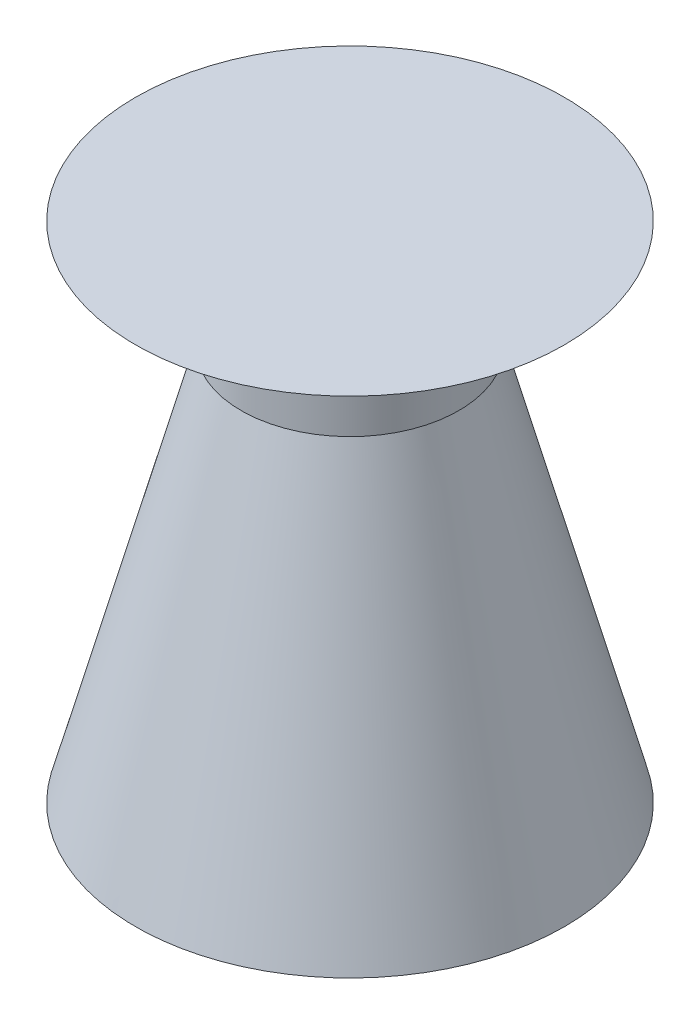
SolidWorks part; units mm, degrees
material "Copper"
ref_plane "Front Plane" through (0, 0, 0) normal (0, 0, 1) x (1, 0, 0)
ref_plane "Top Plane" through (0, 0, 0) normal (0, 1, 0) x (1, 0, 0)
ref_plane "Right Plane" through (0, 0, 0) normal (1, 0, 0) x (0, 0, -1)
sketch "Sketch1" plane through (0, 0, 0) normal (0, 0, 1) x (1, 0, 0)
  line L6 (0, 32.8219) -> (0, -32.8219)
  line L8 (27.94, 32.8219) -> (14.1808, 24.878)
  line L9 (14.1808, 24.878) -> (14.1808, 18.528)
  line L10 (14.1808, 18.528) -> (27.94, -32.8219)
  line L12 (0, 32.8219) -> (27.94, 32.8219)
  line L13 (0, -32.8219) -> (27.94, -32.8219)
  point P4 (0, 0)
  dimension "D1" = 14.1808
  dimension "D2" = 27.94
  dimension "D3" = 15.8877
  dimension "D4" = 6.35
  dimension "D5" = 15
  dimension "D6" = 27.94
revolve "Revolve1" add sketch "Sketch1" angle 360 about L6
